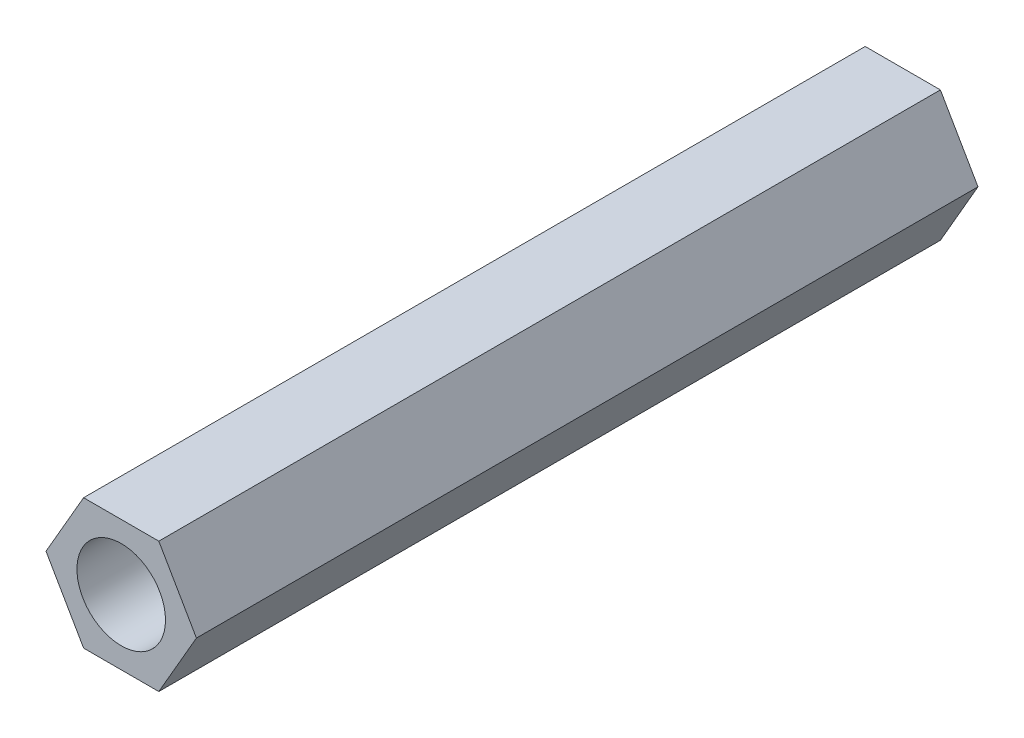
SolidWorks part; units mm, degrees
ref_plane "정면" through (0, 0, 0) normal (0, 0, 1) x (1, 0, 0)
ref_plane "윗면" through (0, 0, 0) normal (0, 1, 0) x (1, 0, 0)
ref_plane "우측면" through (0, 0, 0) normal (1, 0, 0) x (0, 0, -1)
sketch "스케치1" plane through (0, 0, 0) normal (0, 0, 1) x (1, 0, 0)
  line L1 (1.4434, -2.5) -> (2.8868, 0)
  line L2 (2.8868, 0) -> (1.4434, 2.5)
  line L3 (1.4434, 2.5) -> (-1.4434, 2.5)
  line L4 (-1.4434, 2.5) -> (-2.8868, 0)
  line L5 (-2.8868, 0) -> (-1.4434, -2.5)
  line L6 (-1.4434, -2.5) -> (1.4434, -2.5)
  circle A0 centre (0, 0) radius 2.5 construction
  point P1 (0, 0)
  dimension "D1" = 5
extrude "보스-돌출1" add sketch "스케치1" along normal blind 30
sketch "스케치4" plane through (0, 0, 30) normal (0, 0, 1) x (1, 0, 0)
  point P0 (0, 0)
hole_wizard "M3 여유 구멍2" positions "3D스케치5" profile "스케치6" hole size "M3" standard "Ansi Metric" end condition through all
sketch3d "3D스케치5"
  point P0 (0, 0, 0)
  point P3 (0, 0, 30)
sketch "스케치6" plane through (0, 0, 30) normal (1, 0, 0) x (0, -1, 0)
  line L0 (0, 0) -> (0, 30)
  line L1 (0, 30) -> (1.7, 30)
  line L2 (1.7, 30) -> (1.7, 0)
  line L5 (1.7, 0) -> (0, 0)
  line L11 (0, -6.35) -> (0, 107.95) construction
  dimension "관통 구멍 지름" = 3.4
  dimension "관통 구멍 깊이" = 30
